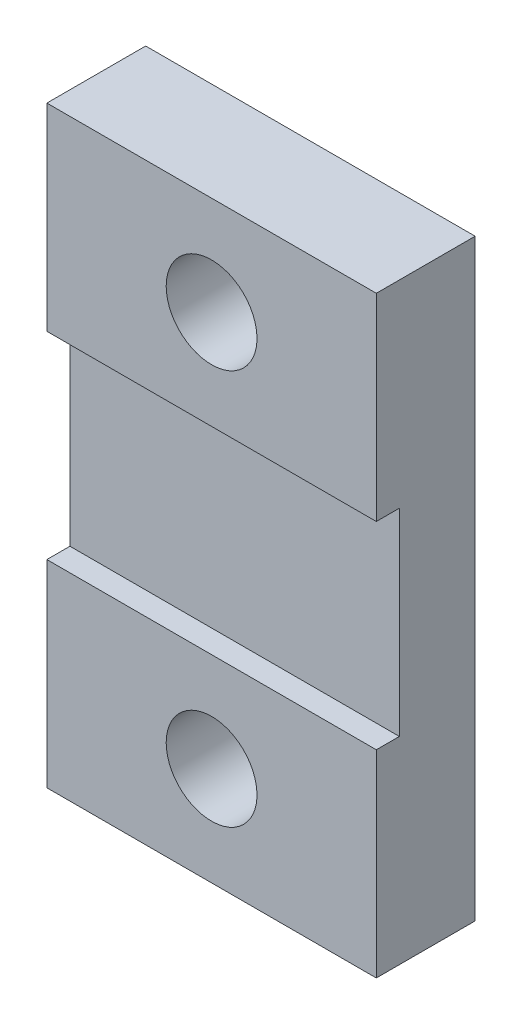
SolidWorks part; units mm, degrees
ref_plane "Front Plane" through (0, 0, 0) normal (0, 0, 1) x (1, 0, 0)
ref_plane "Top Plane" through (0, 0, 0) normal (0, 1, 0) x (1, 0, 0)
ref_plane "Right Plane" through (0, 0, 0) normal (1, 0, 0) x (0, 0, -1)
sketch "Sketch1" plane through (0, 0, 0) normal (0, 0, 1) x (1, 0, 0)
  line L0 (-6.35, 0) -> (6.35, 0) construction
  line L1 (-6.35, -11.43) -> (6.35, -11.43)
  line L2 (-6.35, -11.43) -> (-6.35, 11.43)
  line L3 (-6.35, 11.43) -> (6.35, 11.43)
  line L4 (6.35, -11.43) -> (6.35, 11.43)
  line L5 (-6.35, -11.43) -> (6.35, 11.43) construction
  line L6 (-6.35, 11.43) -> (6.35, -11.43) construction
  circle A0 centre (0, 7.62) radius 1.75
  circle A1 centre (0, -7.62) radius 1.75
  point P0 (0, 0)
  point P10 (0, 0)
  dimension "D3" = 3.5
  dimension "D1" = 22.86
  dimension "D2" = 12.7
  dimension "D4" = 3.81
extrude "Boss-Extrude1" add sketch "Sketch1" along normal blind 3.81
sketch "Sketch2" plane through (0, 0, 3.81) normal (0, 0, 1) x (1, 0, 0)
  line L0 (6.35, -11.43) -> (6.35, 11.43) construction
  line L1 (-6.35, -3.81) -> (6.35, -3.81)
  line L2 (-6.35, -3.81) -> (-6.35, 3.81)
  line L3 (-6.35, 3.81) -> (6.35, 3.81)
  line L4 (6.35, -3.81) -> (6.35, 3.81)
  line L5 (-6.35, -3.81) -> (6.35, 3.81) construction
  line L6 (-6.35, 3.81) -> (6.35, -3.81) construction
  point P0 (0, 0)
  dimension "D1" = 7.62
extrude "Cut-Extrude1" cut sketch "Sketch2" against normal blind 0.889
